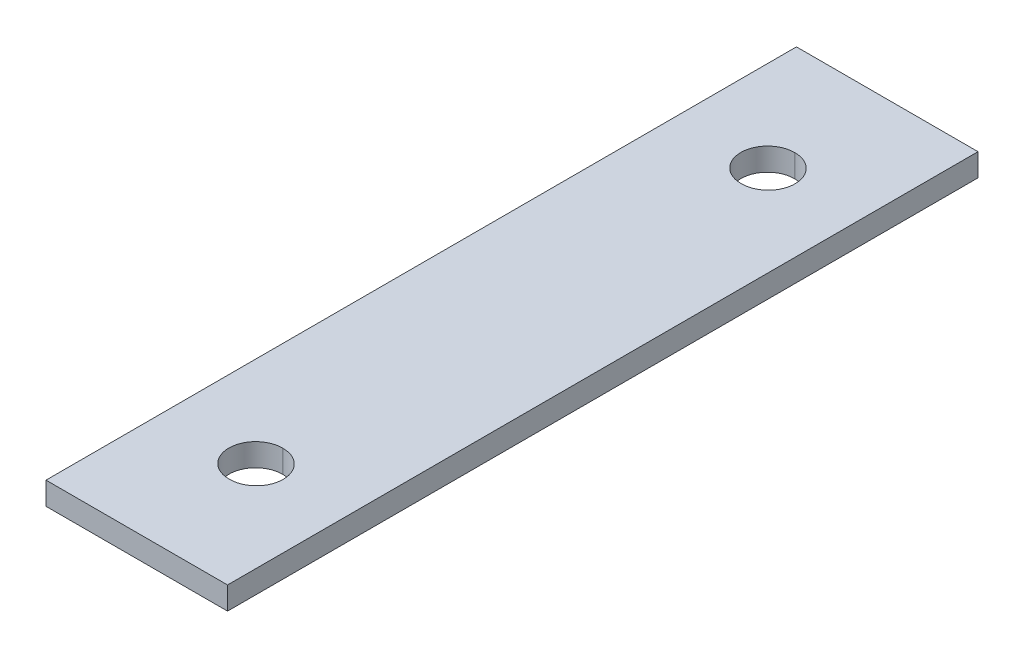
SolidWorks part; units mm, degrees
material "1023 Carbon Steel Sheet (SS)"
ref_plane "Front Plane" through (0, 0, 0) normal (0, 0, 1) x (1, 0, 0)
ref_plane "Top Plane" through (0, 0, 0) normal (0, 1, 0) x (1, 0, 0)
ref_plane "Right Plane" through (0, 0, 0) normal (1, 0, 0) x (0, 0, -1)
sketch "Sketch1" plane through (0, 0, 0) normal (0, 1, 0) x (1, 0, 0)
  line L1 (12.7, -52.5) -> (-12.7, -52.5)
  line L2 (12.7, -52.5) -> (12.7, 52.5)
  line L3 (12.7, 52.5) -> (-12.7, 52.5)
  line L4 (-12.7, -52.5) -> (-12.7, 52.5)
  line L5 (12.7, -52.5) -> (-12.7, 52.5) construction
  line L6 (12.7, 52.5) -> (-12.7, -52.5) construction
  point P0 (0, 0)
  dimension "D1" = 105
  dimension "D2" = 25.4
extrude "Boss-Extrude1" add sketch "Sketch1" along normal blind 3.175
sketch "Sketch2" plane through (0, 3.175, 0) normal (0, 1, 0) x (1, 0, 0)
  line L0 (-0.05, 35.814) -> (0.05, 35.814) construction
  line L1 (-0.05, 39.564) -> (0.05, 39.564)
  line L2 (-0.05, 32.064) -> (0.05, 32.064)
  line L3 (0, 35.814) -> (0, -35.814) construction
  line L4 (-0.05, -35.814) -> (0.05, -35.814) construction
  line L5 (-0.05, -32.064) -> (0.05, -32.064)
  line L6 (-0.05, -39.564) -> (0.05, -39.564)
  arc A0 (-0.05, 39.564) -> (-0.05, 32.064) centre (-0.05, 35.814) ccw
  arc A1 (0.05, 32.064) -> (0.05, 39.564) centre (0.05, 35.814) ccw
  arc A2 (-0.05, -32.064) -> (-0.05, -39.564) centre (-0.05, -35.814) ccw
  arc A3 (0.05, -39.564) -> (0.05, -32.064) centre (0.05, -35.814) ccw
  point P2 (0, 35.814)
  point P11 (0, -35.814)
  point P17 (0, 0)
  point P30 (0, 0)
  dimension "D1" = 7.5
  dimension "D2" = 0.1
  dimension "D3" = 71.628
extrude "Cut-Extrude1" cut sketch "Sketch2" against normal through all
